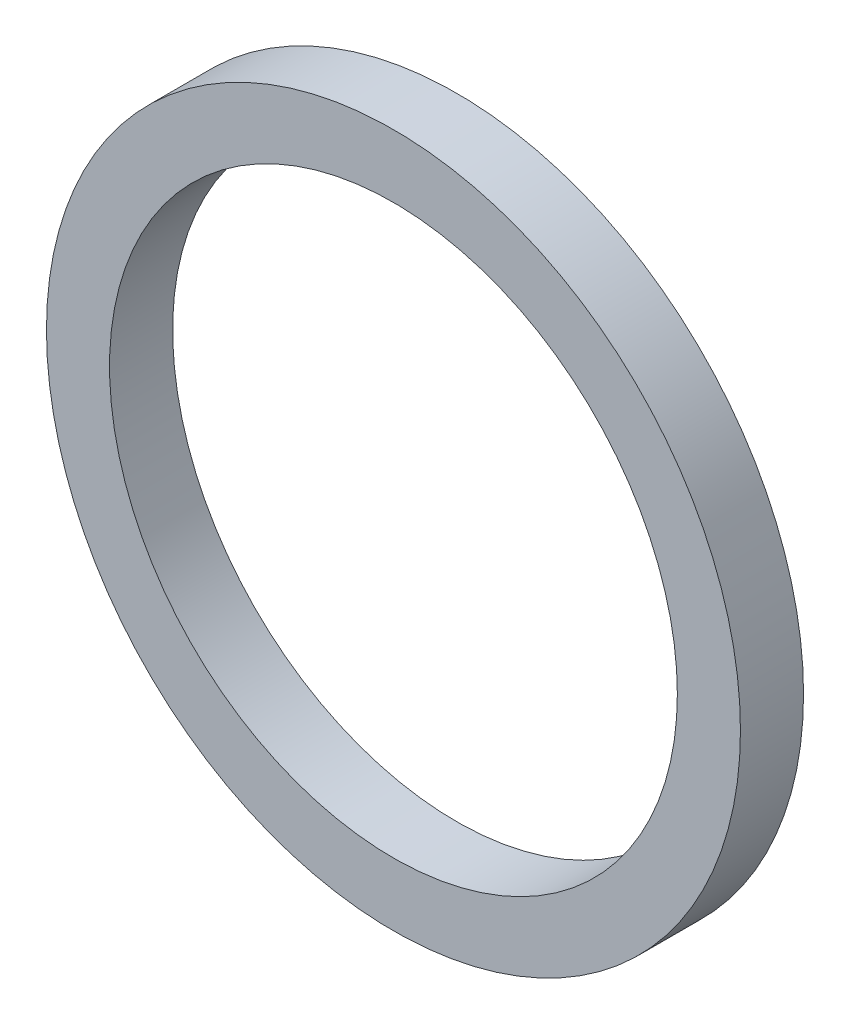
SolidWorks part; units mm, degrees
ref_plane "Płaszczyzna przednia" through (0, 0, 0) normal (0, 0, 1) x (1, 0, 0)
ref_plane "Płaszczyzna górna" through (0, 0, 0) normal (0, 1, 0) x (1, 0, 0)
ref_plane "Płaszczyzna prawa" through (0, 0, 0) normal (1, 0, 0) x (0, 0, -1)
sketch "Szkic1" plane through (0, 0, 0) normal (0, 0, 1) x (1, 0, 0)
  circle A0 centre (0, 0) radius 45
  circle A1 centre (0, 0) radius 55
  dimension "D1" = 90
  dimension "D2" = 10
extrude "Dodanie-wyciągnięcie1" add sketch "Szkic1" along normal blind 10
